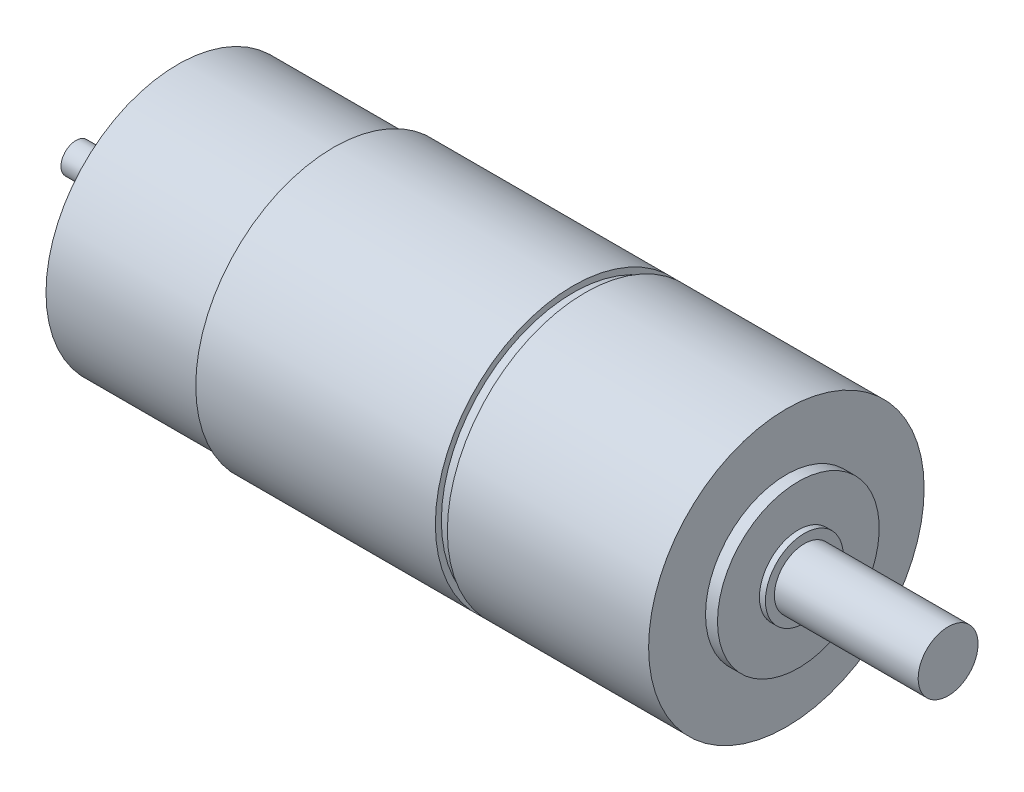
SolidWorks part; units mm, degrees
ref_plane "Front Plane" through (0, 0, 0) normal (0, 0, 1) x (1, 0, 0)
ref_plane "Top Plane" through (0, 0, 0) normal (0, 1, 0) x (1, 0, 0)
ref_plane "Right Plane" through (0, 0, 0) normal (1, 0, 0) x (0, 0, -1)
sketch "Sketch1" plane through (0, 0, 0) normal (0, 1, 0) x (1, 0, 0)
  line L0 (0, 0) -> (0, 2.5)
  line L1 (0, 2.5) -> (10, 2.5)
  line L2 (10, 2.5) -> (10, 5)
  line L3 (10, 5) -> (12, 5)
  line L4 (12, 5) -> (12, 6)
  line L5 (12, 6) -> (17, 6)
  line L6 (17, 6) -> (17, 22)
  line L7 (17, 22) -> (43, 22)
  line L8 (43, 22) -> (43, 23)
  line L9 (43, 23) -> (83, 23)
  line L10 (83, 23) -> (83, 22)
  line L11 (83, 22) -> (85, 22)
  line L12 (85, 23) -> (85, 22)
  line L13 (85, 23) -> (118.6, 23)
  line L14 (118.6, 23) -> (118.6, 13.5)
  line L15 (118.6, 13.5) -> (120.6, 13.5)
  line L16 (120.6, 13.5) -> (120.6, 6.5)
  line L17 (120.6, 6.5) -> (121.6, 6.5)
  line L18 (121.6, 6.5) -> (121.6, 5)
  line L19 (121.6, 5) -> (145.6, 5)
  line L20 (145.6, 5) -> (145.6, 0)
  line L21 (0, 0) -> (145.6, 0)
  line L22 (17, 22) -> (19, 22)
  line L24 (19, 20) -> (19, 0)
  line L25 (19, 20) -> (116.6, 20)
  line L26 (116.6, 20) -> (116.6, 0)
revolve "Revolve1" add sketch "Sketch1" angle 360 about L21
